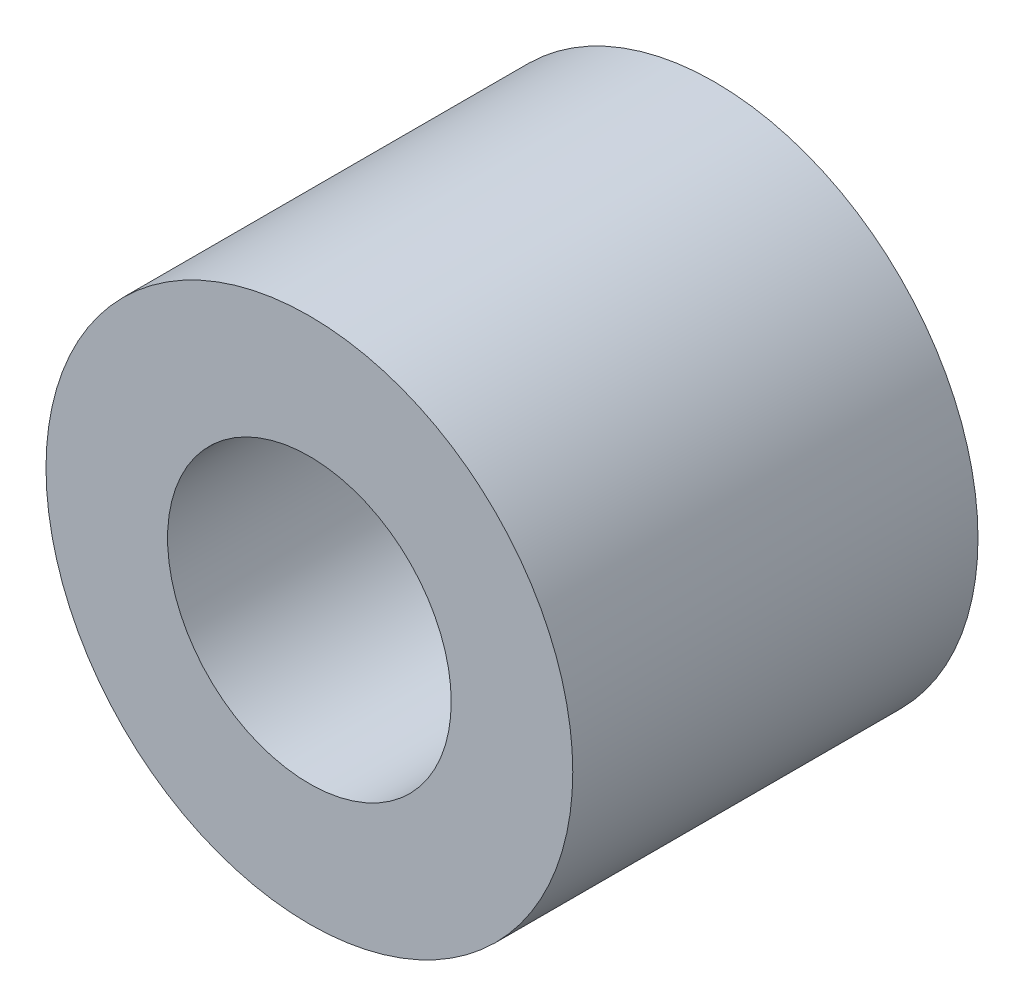
SolidWorks part; units mm, degrees
ref_plane "Piano frontale" through (0, 0, 0) normal (0, 0, 1) x (1, 0, 0)
ref_plane "Piano superiore" through (0, 0, 0) normal (0, 1, 0) x (1, 0, 0)
ref_plane "Piano destro" through (0, 0, 0) normal (1, 0, 0) x (0, 0, -1)
sketch "Schizzo1" plane through (0, 0, 0) normal (0, 0, 1) x (1, 0, 0)
  circle A0 centre (0, 0) radius 1.75
  circle A1 centre (0, 0) radius 3.25
  dimension "D1" = 3.5
  dimension "D2" = 6.5
extrude "Estrusione-Estrusione1" add sketch "Schizzo1" along normal blind 5
